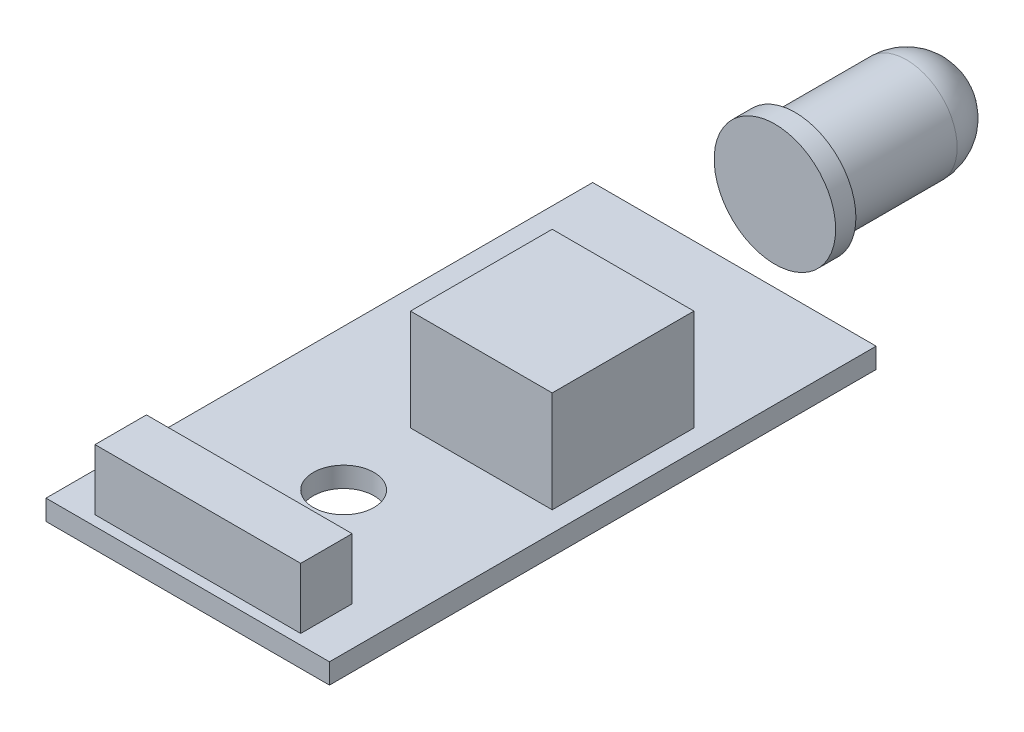
SolidWorks part; units mm, degrees
ref_plane "Front" through (0, 0, 0) normal (0, 0, 1) x (1, 0, 0)
ref_plane "Top" through (0, 0, 0) normal (0, 1, 0) x (1, 0, 0)
ref_plane "Right" through (0, 0, 0) normal (1, 0, 0) x (0, 0, -1)
sketch "Sketch1" plane through (0, 0, 0) normal (0, 1, 0) x (1, 0, 0)
  line L1 (-7, 13.5) -> (7, 13.5)
  line L2 (-7, 13.5) -> (-7, -13.5)
  line L3 (-7, -13.5) -> (7, -13.5)
  line L4 (7, 13.5) -> (7, -13.5)
  line L5 (-7, 13.5) -> (7, -13.5) construction
  line L6 (-7, -13.5) -> (7, 13.5) construction
  point P0 (0, 0)
  dimension "D1" = 27
  dimension "D2" = 14
extrude "Boss-Extrude1" add sketch "Sketch1" along normal blind 1
sketch "Sketch2" plane through (0, 1, 0) normal (0, 1, 0) x (1, 0, 0)
  line L1 (-7, -13.5) -> (7, -13.5) construction
  circle A0 centre (0, -5.8) radius 1.5
  point P4 (0, 0)
  dimension "D1" = 3
  dimension "D2" = 6.2
extrude "Cut-Extrude1" cut sketch "Sketch2" against normal through all
sketch "Sketch3" plane through (0, 1, 0) normal (0, 1, 0) x (1, 0, 0)
  line L0 (7, -13.5) -> (7, 13.5) construction
  line L1 (-1, 5.5) -> (6, 5.5)
  line L2 (-1, 5.5) -> (-1, -1.5)
  line L3 (-1, -1.5) -> (6, -1.5)
  line L4 (6, 5.5) -> (6, -1.5)
  line L5 (7, 13.5) -> (-7, 13.5) construction
  point P4 (-0.9574, 5.5561)
  dimension "D1" = 7
  dimension "D2" = 1
  dimension "D3" = 8
extrude "Boss-Extrude2" add sketch "Sketch3" along normal blind 5
sketch "Sketch4" plane through (0, 1, 0) normal (0, 1, 0) x (1, 0, 0)
  line L0 (-7, -13.5) -> (7, -13.5) construction
  line L1 (-5.08, -10.46) -> (5.08, -10.46)
  line L2 (-5.08, -10.46) -> (-5.08, -13)
  line L3 (-5.08, -13) -> (5.08, -13)
  line L4 (5.08, -10.46) -> (5.08, -13)
  line L5 (-5.08, -10.46) -> (5.08, -13) construction
  line L6 (-5.08, -13) -> (5.08, -10.46) construction
  point P0 (0, -11.73)
  point P5 (0, 0)
  point P6 (0, -11.2319)
  dimension "D1" = 10.16
  dimension "D2" = 2.54
  dimension "D3" = 0.5
extrude "Boss-Extrude3" add sketch "Sketch4" along normal blind 3
sketch "Sketch5" plane through (0, 0, 0) normal (1, 0, 0) x (0, 0, -1)
  line L0 (15.5, 3) -> (24.5, 3) construction
  line L1 (15.5, 3) -> (15.5, 6)
  line L2 (15.5, 6) -> (16.5, 6)
  line L3 (16.5, 6) -> (16.5, 5.5)
  line L4 (16.5, 5.5) -> (22, 5.5)
  line L5 (13.5, 1) -> (13.5, 0) construction
  line L6 (-13.5, 0) -> (13.5, 0) construction
  line L7 (15.5, 3) -> (24.5, 3)
  arc A0 (22, 5.5) -> (24.5, 3) centre (22, 3) cw
  point P7 (0, 0)
  dimension "D1" = 5
  dimension "D2" = 6
  dimension "D3" = 1
  dimension "D4" = 9
  dimension "D5" = 2
  dimension "D6" = 3
revolve "Revolve1" add sketch "Sketch5" angle 360 about L0
